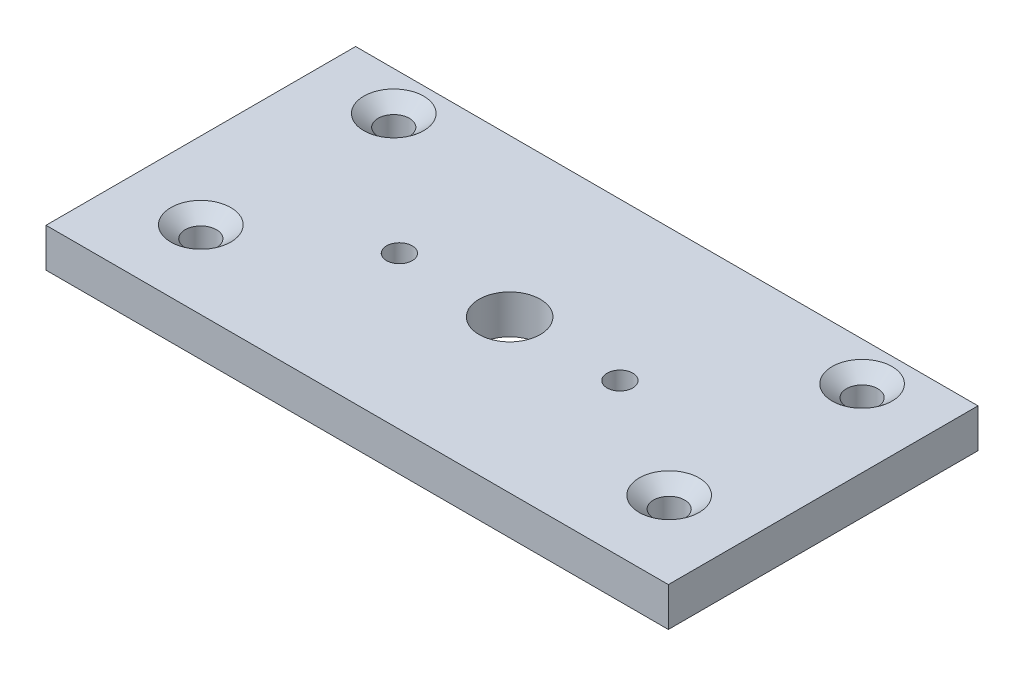
SolidWorks part; units mm, degrees
ref_plane "Front Plane" through (0, 0, 0) normal (0, 0, 1) x (1, 0, 0)
ref_plane "Top Plane" through (0, 0, 0) normal (0, 1, 0) x (1, 0, 0)
ref_plane "Right Plane" through (0, 0, 0) normal (1, 0, 0) x (0, 0, -1)
sketch "Sketch1" plane through (0, 0, 0) normal (0, 1, 0) x (1, 0, 0)
  line L1 (0, 0) -> (101.6, 0)
  line L2 (0, 0) -> (0, 50.546)
  line L3 (0, 50.546) -> (101.6, 50.546)
  line L4 (101.6, 0) -> (101.6, 50.546)
  dimension "D1" = 101.6
  dimension "D2" = 50.546
extrude "base" add sketch "Sketch1" along normal blind 6.35
hole_wizard "bearing_block_bolt_hole_pattern" positions "Sketch3" profile "Sketch4" tap size "M5x0.8" standard "ANSI Metric" end condition through all
sketch "Sketch3" plane through (0, 6.35, 0) normal (0, 1, 0) x (1, 0, 0)
  line L0 (32.8, 24.892) -> (68.8, 24.892)
  line L1 (50.8, 24.892) -> (50.8, 50.546)
  line L2 (101.6, 50.546) -> (0, 50.546) construction
  point P1 (32.8, 24.892)
  point P2 (68.8, 24.892)
  point P20 (0, 0)
  point P21 (0, 0)
  point P22 (0, 0)
  dimension "D1" = 35.9999
  dimension "D2" = 25.654
sketch "Sketch4" plane through (32.8, 6.35, -24.892) normal (1, 0, 0) x (0, 0, 1)
  line L0 (0, 0) -> (0, 6.35)
  line L1 (0, 6.35) -> (2.1, 6.35)
  line L2 (2.1, 6.35) -> (2.1, 0)
  line L5 (2.1, 0) -> (0, 0)
  line L11 (0, -6.35) -> (0, 107.95) construction
  dimension "Thru Tap Drill Dia." = 4.2
  dimension "Thru Tap Drill Depth" = 6.35
cosmetic thread "Hole Thread1" parameters "D2"=5
cosmetic thread "Hole Thread2" parameters "D2"=5
hole_wizard "shaft_clearance_hole" positions "Sketch5" profile "Sketch6" hole size "Ø10.0" standard "ANSI Metric" end condition through all
sketch "Sketch5" plane through (0, 6.35, 0) normal (0, 1, 0) x (1, 0, 0)
  line L1 (32.8, 24.892) -> (68.8, 24.892)
  point P0 (50.8, 24.892)
  point P11 (0, 0)
  point P14 (51.5581, 13.8469)
  point P16 (0, 0)
sketch "Sketch6" plane through (50.8, 6.35, -24.892) normal (1, 0, 0) x (0, 0, 1)
  line L0 (0, 0) -> (0, 6.35)
  line L1 (0, 6.35) -> (5, 6.35)
  line L2 (5, 6.35) -> (5, 0)
  line L5 (5, 0) -> (0, 0)
  line L11 (0, -6.35) -> (0, 107.95) construction
  dimension "Thru Hole Dia." = 10
  dimension "Thru Hole Depth" = 6.35
hole_wizard "plate_mounting_wood_screw_clearance_holes" positions "Sketch11" profile "Sketch10" countersink size "#10" standard "ANSI Inch" end condition through all
sketch "Sketch11" plane through (0, 6.35, 0) normal (0, 1, 0) x (1, 0, 0)
  line L1 (12.573, 44.196) -> (89.027, 44.196)
  line L2 (12.573, 44.196) -> (12.573, 12.7)
  line L3 (12.573, 12.7) -> (89.027, 12.7)
  line L4 (89.027, 44.196) -> (89.027, 12.7)
  line L5 (101.6, 50.546) -> (0, 50.546) construction
  line L6 (0, 0) -> (101.6, 0) construction
  point P0 (12.573, 44.196)
  point P1 (89.027, 12.7)
  point P50 (12.573, 12.7)
  point P51 (89.027, 44.196)
  point P70 (50.8, 50.546)
  point P71 (50.8, 44.196)
  dimension "D1" = 76.454
  dimension "D2" = 6.35
  dimension "D3" = 12.7
sketch "Sketch10" plane through (12.573, 6.35, -44.196) normal (1, 0, 0) x (0, 0, 1)
  line L0 (0, 0) -> (0, 6.35)
  line L1 (0, 6.35) -> (2.5527, 6.35)
  line L2 (2.5527, 6.35) -> (2.5527, 1.9608)
  line L3 (2.5527, 1.9608) -> (4.8895, 0)
  line L5 (4.8895, 0) -> (0, 0)
  line L6 (-2.5527, 1.9608) -> (-4.8895, 0) construction
  line L11 (0, -6.35) -> (0, 107.95) construction
  dimension "Thru Hole Dia." = 5.1054
  dimension "Thru Hole Depth" = 6.35
  dimension "Near C'Sink Dia." = 9.779
  dimension "Near C'Sink Angle" = 100
equation "\"baseplate_thickness\"=0.47"
equation "\"baseplate_length\"= 12"
equation "\"baseplate_width\"= 4"
equation "\"rail_width\" = 1"
equation "\"rail_radial_clearance\" = 0.25"
equation "\"slider_width\"= 2"
equation "\"slider_length\"= 4"
equation "\"slider_thickness\"= 1"
equation "\"side_radial_clearance\"= 0.01"
equation "\"front_radial_clearance\"= 0.01"
equation "\"side_plate_width\"= (\"baseplate_width\" - \"slider_width\" - ( 2 * \"side_radial_clearance\" ))/2"
equation "\"side_plate_height\"= \"slider_thickness\" + ( 2 * \"front_radial_clearance\" )"
equation "\"keeper_plate_thickness\" = 0.5"
equation "\"keeper_plate_width\" = (\"baseplate_width\" - \"rail_width\" -  2 * \"rail_radial_clearance\")/2"
equation "\"rail_height\" = 3"
equation "\"D1@Sketch1\"=\"baseplate_width\""
equation "\"D2@Sketch1\"=\"baseplate_thickness\"+\"side_plate_height\"+\"keeper_plate_thickness\""
equation "\"endplate_thickness\"=0.25"
equation "\"D1@base\" = \"endplate_thickness\""
equation "\"bearing_block_hole_distance\"=1.41732"
equation "\"D1@Sketch3\"=\"bearing_block_hole_distance\""
equation "\"D2@Sketch3\"=\"keeper_plate_thickness\"+0.5 * \"side_plate_height\""
equation "\"D1@Sketch11\"=\"baseplate_width\"-\"side_plate_width\""
equation "\"D2@Sketch11\"=0.5 * \"keeper_plate_thickness\""
